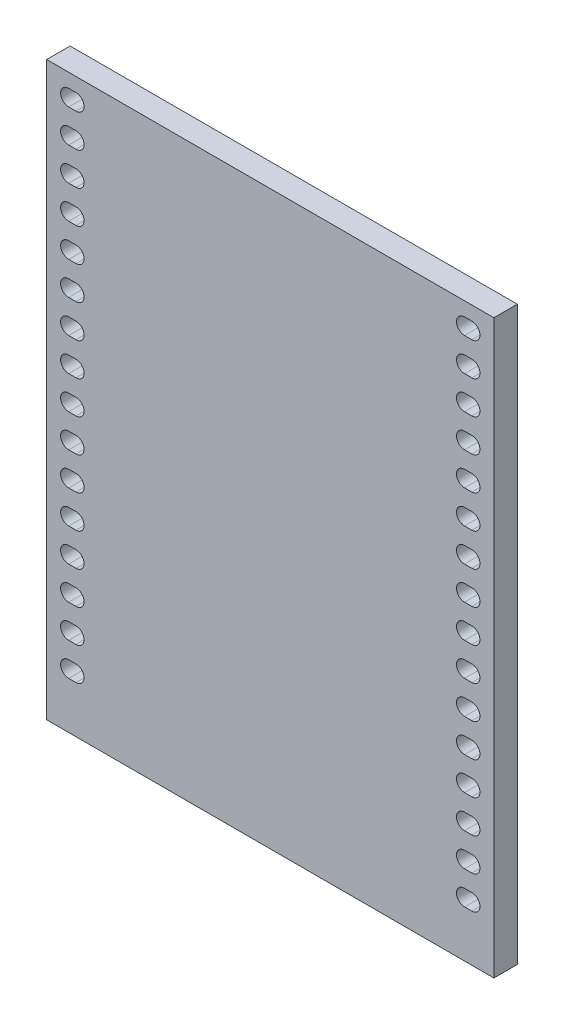
SolidWorks part; units mm, degrees
ref_plane "Front Plane" through (0, 0, 0) normal (0, 0, 1) x (1, 0, 0)
ref_plane "Top Plane" through (0, 0, 0) normal (0, 1, 0) x (1, 0, 0)
ref_plane "Right Plane" through (0, 0, 0) normal (1, 0, 0) x (0, 0, -1)
other "Bounding Box"
ref_plane "Default Plane" through (152.5, 0, 0) normal (-1, 0, 0) x (0, 0, 1)
sketch "Sketch1" plane through (0, 0, 0) normal (0, 0, 1) x (1, 0, 0)
  line L1 (-152.5, 0) -> (152.5, 0)
  line L2 (-152.5, 0) -> (-152.5, 390)
  line L3 (-152.5, 390) -> (152.5, 390)
  line L4 (152.5, 0) -> (152.5, 390)
  point P4 (0, 0)
  dimension "D1" = 305
  dimension "D2" = 390
extrude "Boss-Extrude1" add sketch "Sketch1" along normal blind 16
sketch "Sketch2" plane through (0, 0, 16) normal (0, 0, 1) x (1, 0, 0)
  line L0 (152.5, 0) -> (152.5, 37.5) construction
  line L1 (152.5, 0) -> (152.5, 390) construction
  line L2 (152.5, 37.5) -> (137.5, 37.5) construction
  line L3 (-152.5, 0) -> (152.5, 0) construction
  line L4 (137.5, 37.5) -> (132.5, 37.5) construction
  line L5 (137.5, 32) -> (132.5, 32)
  line L6 (137.5, 43) -> (132.5, 43)
  circle A0 centre (137.5, 37.5) radius 5.5 construction
  arc A1 (137.5, 32) -> (137.5, 43) centre (137.5, 37.5) ccw
  arc A2 (132.5, 43) -> (132.5, 32) centre (132.5, 37.5) ccw
  point P8 (135, 37.5)
  dimension "D1" = 11
  dimension "D2" = 37.5
  dimension "D3" = 15
  dimension "D4" = 5
extrude "Cut-Extrude4" cut sketch "Sketch2" against normal through all
pattern_linear "LPattern1" count 16 spacing 22.5 along (0, 1, 0) of "Cut-Extrude4"
hole_wizard "#8-36 Tapped Hole1" positions "Sketch5" profile "Sketch4" tap size "#8-36" standard "ANSI Inch"
sketch "Sketch5" plane through (0, 0, 0) normal (0, -1, 0) x (-1, 0, 0)
  line L0 (-125, -8) -> (125, -8) construction
  line L2 (0, -8) -> (0, 14.7833) construction
  line L4 (-152.5, -16) -> (-152.5, 0) construction
  line L5 (152.5, -16) -> (152.5, 0) construction
  line L6 (152.5, -16) -> (-152.5, -16) construction
  line L7 (152.5, 0) -> (-152.5, 0) construction
  point P0 (-125, -8)
  point P2 (0, -8)
  point P4 (125, -8)
  dimension "D1" = 250
sketch "Sketch4" plane through (125, 0, 8) normal (1, 0, 0) x (0, 0, -1)
  line L0 (0, 0) -> (0, 26.0378)
  line L1 (0, 26.0378) -> (1.7272, 25)
  line L2 (1.7272, 25) -> (1.7272, 0)
  line L5 (1.7272, 0) -> (0, 0)
  line L10 (0, 26.0378) -> (-1.7272, 25) construction
  line L11 (0, -6.35) -> (0, 107.95) construction
  dimension "Tap Drill Dia." = 3.4544
  dimension "Tap Drill Depth" = 25
  dimension "Drill Angle" = 118
cosmetic thread "Hole Thread1" parameters "D1"=20, "D2"=4.1656
cosmetic thread "Hole Thread2" parameters "D1"=20, "D2"=4.1656
cosmetic thread "Hole Thread3" parameters "D1"=20, "D2"=4.1656
mirror "Mirror1" about plane through (0, 0, 0) normal (1, 0, 0) of "LPattern1", "Cut-Extrude4"
